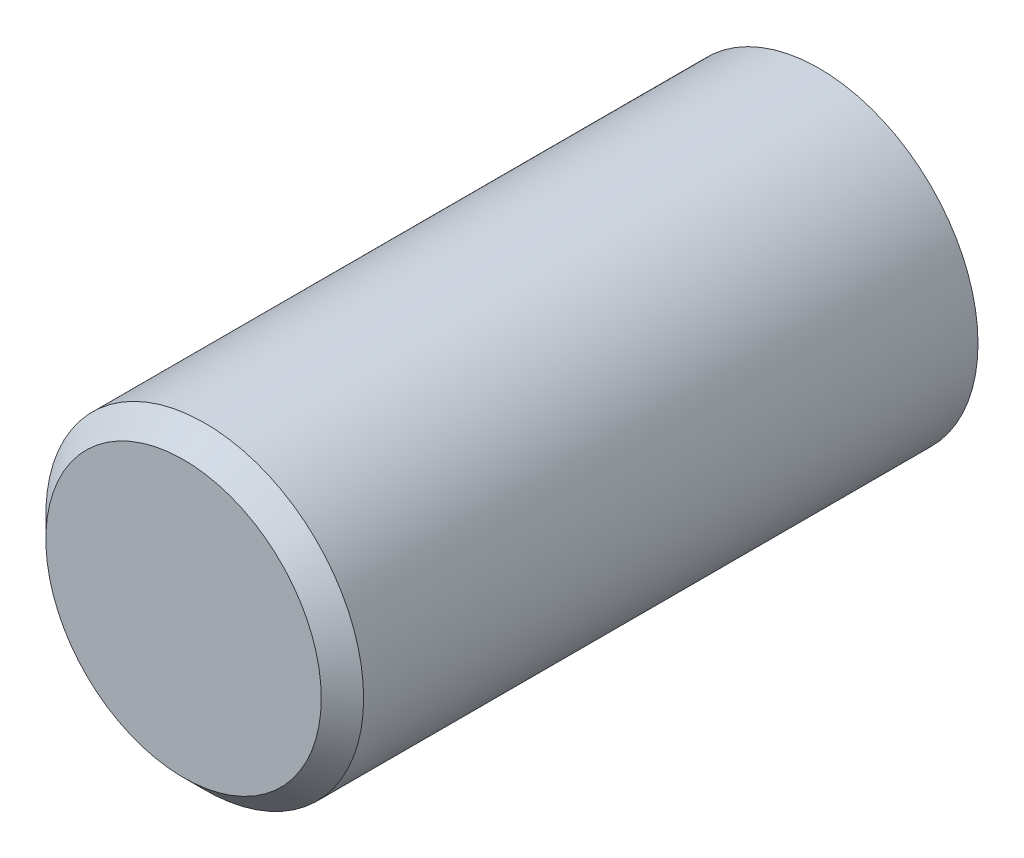
SolidWorks part; units mm, degrees
ref_plane "Front Plane" through (0, 0, 0) normal (0, 0, 1) x (1, 0, 0)
ref_plane "Top Plane" through (0, 0, 0) normal (0, 1, 0) x (1, 0, 0)
ref_plane "Right Plane" through (0, 0, 0) normal (1, 0, 0) x (0, 0, -1)
sketch "Sketch1" plane through (0, 0, 0) normal (0, 0, 1) x (1, 0, 0)
  circle A0 centre (0, 0) radius 1.5
  dimension "D1" = 3
extrude "Boss-Extrude1" add sketch "Sketch1" along normal blind 6
chamfer "Chamfer1" distance 0.2 angle 45 1 edges at (1.5, 0, 6)
